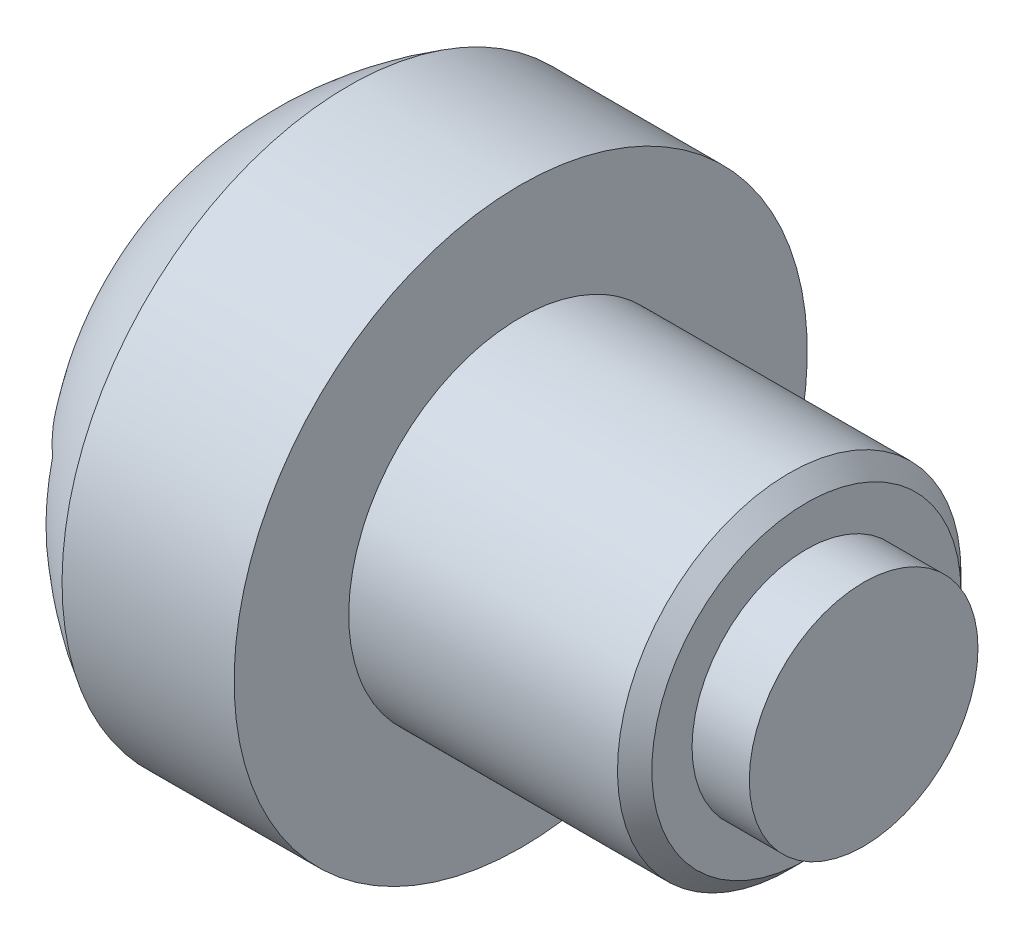
SolidWorks part; units mm, degrees
ref_plane "Front Plane" through (0, 0, 0) normal (0, 0, 1) x (1, 0, 0)
ref_plane "Top Plane" through (0, 0, 0) normal (0, 1, 0) x (1, 0, 0)
ref_plane "Right Plane" through (0, 0, 0) normal (1, 0, 0) x (0, 0, -1)
sketch "Sketch2" plane through (0, 0, 0) normal (0, 0, 1) x (1, 0, 0)
  line L0 (-4.5, 1.2079) -> (4.5, 1.2256) construction
  line L1 (-1.5, -3.7744) -> (1.5, -3.7744)
  line L2 (-1.5, -3.7744) -> (-1.5, 6.2256)
  line L3 (-1.5, 6.2256) -> (1.5, 6.2256)
  line L4 (1.5, -3.7744) -> (1.5, 6.2256)
  arc A0 (-1.5, 6.2256) -> (-4.5, 1.2079) centre (1.4973, 1.0279) ccw
  arc A1 (-1.5, -3.7744) -> (-4.5, 1.2079) centre (1.4961, 1.424) cw
  point P0 (0, 0)
  dimension "D8" = 6
  dimension "D2" = 10
  dimension "D9" = 3
revolve "Revolve2" add sketch "Sketch2" angle 360 about L0
ref_plane "Plane1" through (-4.3, 0, 0) normal (-1, 0, 0) x (0, 0, 1)
sketch "Sketch16" plane through (-4.3, 0, 0) normal (-1, 0, 0) x (0, 0, 1)
  line L0 (-5.0118, 2.2079) -> (-5.0118, 0.2079)
  line L1 (-5.0118, 0.2079) -> (5.0118, 0.2079)
  line L2 (5.0118, 0.2079) -> (5.0118, 2.2079)
  line L4 (-5.0118, 2.2079) -> (5.0118, 2.2079)
  dimension "D1" = 2
extrude "Cut-Extrude2" cut sketch "Sketch16" against normal blind 1.81 and the other way blind 2
ref_plane "Plane3" through (3.5, 0, 0) normal (1, 0, 0) x (0, 0, -1)
ref_plane "Plane5" through (1.5, 0, 0) normal (1, 0, 0) x (0, 0, -1)
sketch "Sketch25" plane through (1.5, 0, 0) normal (1, 0, 0) x (0, 0, -1)
  circle A0 centre (0, 1.2197) radius 3
extrude "Boss-Extrude4" add sketch "Sketch25" along normal blind 5
chamfer "Chamfer1" distance 0.3 angle 45 1 edges at (6.5, 1.2197, -3)
sketch "Sketch43" plane through (6.5, 0, 0) normal (1, 0, 0) x (0, 0, -1)
  circle A0 centre (0, 1.2197) radius 1.9975
extrude "Boss-Extrude6" add sketch "Sketch43" along normal blind 1
